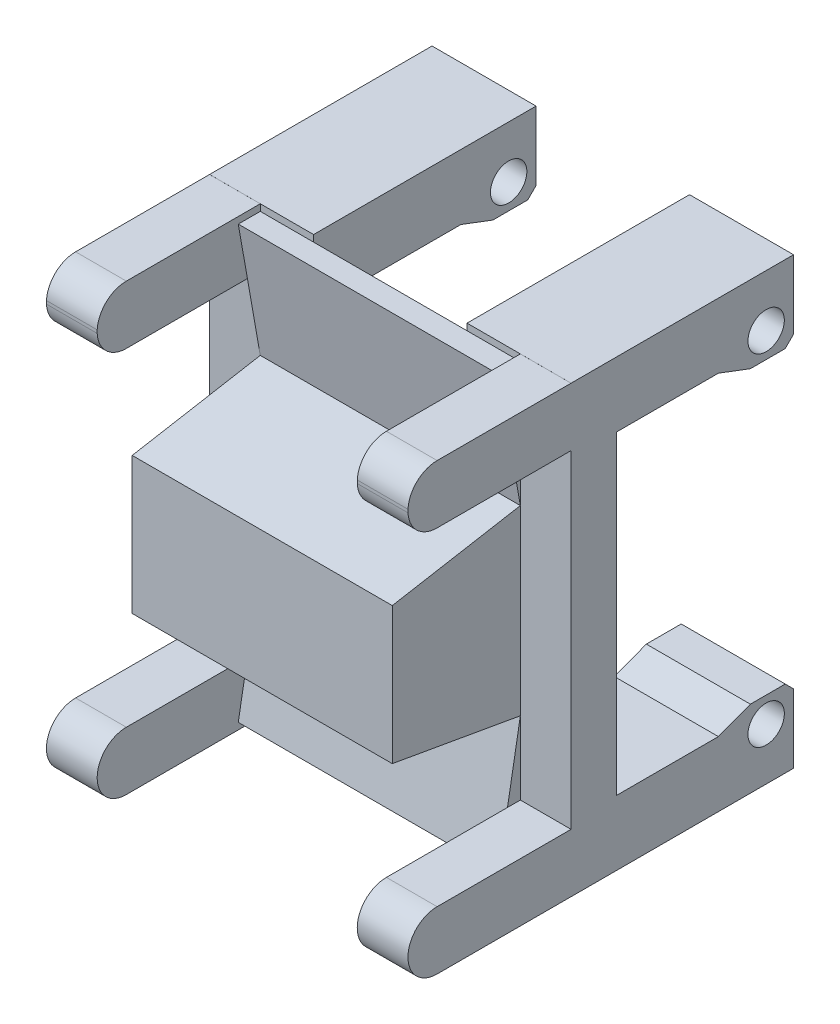
SolidWorks part; units mm, degrees
ref_plane "前视基准面" through (0, 0, 0) normal (0, 0, 1) x (1, 0, 0)
ref_plane "上视基准面" through (0, 0, 0) normal (0, 1, 0) x (1, 0, 0)
ref_plane "右视基准面" through (0, 0, 0) normal (1, 0, 0) x (0, 0, -1)
sketch "草图1" plane through (0, 0, 0) normal (0, 0, 1) x (1, 0, 0)
  line L1 (13.9, -12.1) -> (-13.9, -12.1)
  line L2 (13.9, -12.1) -> (13.9, 12.1)
  line L3 (13.9, 12.1) -> (-13.9, 12.1)
  line L4 (-13.9, -12.1) -> (-13.9, 12.1)
  point P0 (0, 0)
  dimension "D1" = 27.8
  dimension "D2" = 24.2
extrude "凸台-拉伸1" add sketch "草图1" along normal blind 5
sketch "草图5" plane through (-13.9, 0, 0) normal (-1, 0, 0) x (0, 0, 1)
  line L0 (-12.9679, -11.169) -> (-13.6089, -11.8099)
  line L1 (5, -12.1) -> (-7.8276, -12.1)
  line L2 (5, -12.1) -> (5, -17.1)
  line L3 (5, -17.1) -> (-11.5, -17.1)
  line L5 (-10.2868, -11.169) -> (-7.8276, -12.1)
  line L6 (-11.5, -17.1) -> (-13.6089, -17.1)
  line L8 (-11.5, -11.169) -> (-12.9679, -11.169)
  line L9 (-13.6089, -17.1) -> (-13.6089, -11.8099)
  line L10 (-11.5, -11.169) -> (-10.2868, -11.169)
  line L15 (-5.1027, 0) -> (13.2164, 0)
  line L16 (5, 17.1) -> (-11.5, 17.1)
  line L17 (5, 12.1) -> (5, 17.1)
  line L18 (5, 12.1) -> (-7.8276, 12.1)
  line L19 (-10.2868, 11.169) -> (-7.8276, 12.1)
  line L20 (-11.5, 11.169) -> (-10.2868, 11.169)
  line L21 (-11.5, 11.169) -> (-12.9679, 11.169)
  line L22 (-12.9679, 11.169) -> (-13.6089, 11.8099)
  line L23 (-13.6089, 17.1) -> (-13.6089, 11.8099)
  line L24 (-11.5, 17.1) -> (-13.6089, 17.1)
  circle A0 centre (-11.5, -13.1) radius 1.4
  circle A1 centre (-11.5, 13.1) radius 1.4
  line M15 (0, -12.1) -> (5, -12.1)
  line M17 (5, 12.1) -> (0, 12.1)
extrude "凸台-拉伸5" add sketch "草图5" against normal blind 8 contours L10 L8 L0 L9 L6 L3 L2 L1 L5 A0 M15 | L16 L24 L23 L22 L21 L20 L19 L18 L17 A1 M17
mirror "镜向1" about plane through (0, 0, 0) normal (1, 0, 0) of "凸台-拉伸5"
sketch "草图8" plane through (13.9, 0, 0) normal (1, 0, 0) x (0, 0, -1)
  line L0 (-3.5, 17.1) -> (-3.5, -17.1)
  line L1 (-5, 17.1) -> (-5, -17.1)
  line L3 (-5, 17.1) -> (-3.5, 17.1)
  line L4 (-5, 17.1) -> (13.6089, 17.1) construction
  line L5 (-5, -17.1) -> (-3.5, -17.1)
  line L6 (-5, -17.1) -> (13.6089, -17.1) construction
  dimension "D1" = 1.5
extrude "切除-拉伸1" cut sketch "草图8" against normal blind 30
sketch "草图10" plane through (0, 0, 0) normal (1, 0, 0) x (0, 0, -1)
  line L0 (-13.6028, 0) -> (-13.3481, 0)
  line L1 (-3.5, -7) -> (-3.5, 7)
  line L2 (-3.5, -17.1) -> (-3.5, 17.1) construction
  line L3 (-3.5, 7) -> (-5.1912, 16.5913)
  line L4 (-5.1912, 16.5913) -> (-3.5, 16.5913)
  line L5 (-3.5, 16.5913) -> (-3.5, 7)
  line L6 (-5.1912, 16.5913) -> (-3.5, 7)
  line L8 (-3.5, 7) -> (-13.3481, 5.2635)
  line L10 (-13.3481, 5.2635) -> (-13.3481, -5.2635)
  line L11 (-5.1912, -16.5913) -> (-3.5, -16.5913)
  line L12 (-3.5, -7) -> (-5.1912, -16.5913)
  line L13 (-3.5, -16.5913) -> (-3.5, -7)
  line L14 (-3.5, -7) -> (-13.3481, -5.2635)
  point P14 (-3.5, 0)
  point P15 (-13.3481, 0)
  dimension "D1" = 7
  dimension "D2" = 10
extrude "凸台-拉伸11" add sketch "草图10" along normal blind 10 and the other way blind 10 contours L14 L1 L8 L10 | L5 L4 L3 | L11 L13 L12
sketch "草图11" plane through (-10, 0, 0) normal (-1, 0, 0) x (0, 0, 1)
  line L7 (3.5, 12.6115) -> (13.8004, 12.6115)
  line L9 (3.5, 12.6115) -> (3.5, 17.0978)
  line L10 (3.5, 17.0978) -> (13.8004, 17.0978)
  line L11 (16.0404, 14.7357) -> (16.0404, 14.9736)
  line L12 (3.5, -12.6115) -> (3.5, -17.0978)
  line L13 (3.5, -17.0978) -> (13.8004, -17.0978)
  line L14 (3.5, -12.6115) -> (13.8004, -12.6115)
  arc A0 (13.8004, 17.0978) -> (13.8004, 12.6115) centre (13.8004, 14.8547) cw
  arc A1 (13.8004, -17.0978) -> (13.8004, -12.6115) centre (13.8004, -14.8547) ccw
  line M11 (3.5, 16.5913) -> (3.5, 7)
  line M12 (3.5, 7) -> (5.1912, 16.5913)
  line M13 (5.1912, 16.5913) -> (3.5, 16.5913)
extrude "凸台-拉伸12" add sketch "草图11" along normal blind 3.9 contours A0 L11 L10 L9 L7 M13 M12 | L13 A1 L14 L12 | L7 M11 M12 M13
mirror "镜向3" about plane through (0, 0, 0) normal (1, 0, 0) of "凸台-拉伸12"
